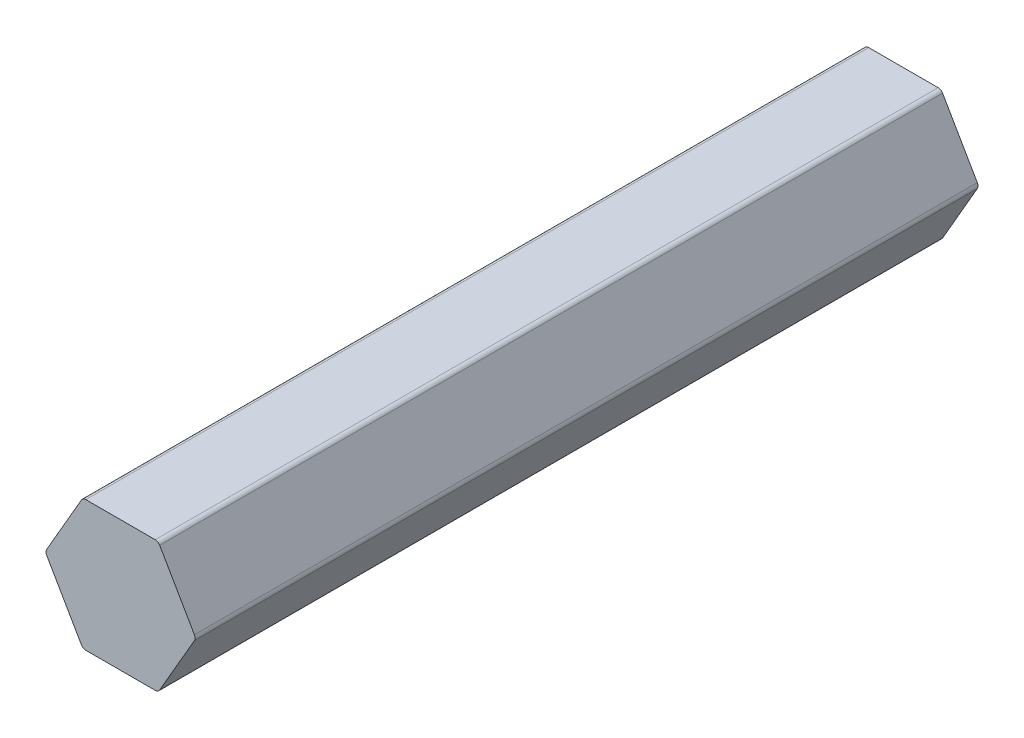
SolidWorks part; units mm, degrees
ref_plane "Front Plane" through (0, 0, 0) normal (0, 0, 1) x (1, 0, 0)
ref_plane "Top Plane" through (0, 0, 0) normal (0, 1, 0) x (1, 0, 0)
ref_plane "Right Plane" through (0, 0, 0) normal (1, 0, 0) x (0, 0, -1)
sketch "Sketch1" plane through (0, 0, 0) normal (0, 0, 1) x (1, 0, 0)
  line L1 (7.3323, 0) -> (3.6662, 6.35)
  line L2 (3.6662, 6.35) -> (-3.6662, 6.35)
  line L3 (-3.6662, 6.35) -> (-7.3323, 0)
  line L4 (-7.3323, 0) -> (-3.6662, -6.35)
  line L5 (-3.6662, -6.35) -> (3.6662, -6.35)
  line L6 (3.6662, -6.35) -> (7.3323, 0)
  circle A0 centre (0, 0) radius 6.35 construction
  point P1 (0, 0)
  dimension "D1" = 12.7
extrude "Boss-Extrude1" add sketch "Sketch1" along normal mid plane 76.2
fillet "Fillet1" radius 0.5 6 edges at (3.6662, -6.35, 0) (-3.6662, -6.35, 0) (-7.3323, 0, 0) (-3.6662, 6.35, 0) (7.3323, 0, 0) (3.6662, 6.35, 0)
